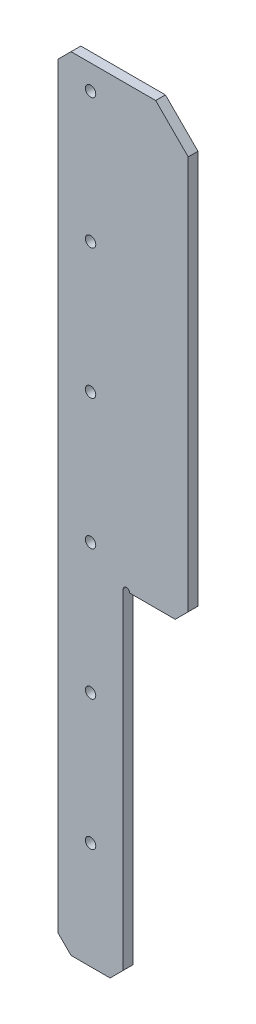
SolidWorks part; units mm, degrees
ref_plane "前视基准面" through (0, 0, 0) normal (0, 0, 1) x (1, 0, 0)
ref_plane "上视基准面" through (0, 0, 0) normal (0, 1, 0) x (1, 0, 0)
ref_plane "右视基准面" through (0, 0, 0) normal (1, 0, 0) x (0, 0, -1)
sketch "草图1" plane through (0, 0, 0) normal (0, 0, 1) x (1, 0, 0)
  line L0 (-20, 135) -> (-20, -105.4)
  line L1 (-20, -105.4) -> (0, -105.4)
  line L2 (0, -105.4) -> (0, 0)
  line L3 (0, 0) -> (20, 0)
  line L4 (20, 0) -> (20, 135)
  line L5 (20, 135) -> (-20, 135)
  point P6 (0, 135)
  dimension "D1" = 40
  dimension "D2" = 135
  dimension "D3" = 240.4
extrude "凸台-拉伸1" add sketch "草图1" along normal mid plane 3
sketch "草图2" plane through (0, 0, 1.5) normal (0, 0, 1) x (1, 0, 0)
  line L0 (20, 135) -> (-20, 135) construction
  line L1 (-20, 135) -> (-20, -105.4) construction
  circle A0 centre (-10, 127.5) radius 1.6
  dimension "D1" = 7.5
  dimension "D2" = 10
  dimension "D3" = 3.2
extrude "切除-拉伸1" cut sketch "草图2" against normal through all
pattern_linear "阵列(线性)1" count 6 spacing 40 along (0, -1, 0) of "切除-拉伸1"
chamfer "倒角1" distance 10 angle 45 1 edges at (20, 135, 0)
chamfer "倒角2" distance 4 angle 45 4 edges at (20, 0, 0) (0, -105.4, 0) (-20, -105.4, 0) (-20, 135, 0)
sketch "草图3" plane through (0, 0, 1.5) normal (0, 0, 1) x (1, 0, 0)
  line L0 (0, 0) -> (16, 0) construction
  circle A0 centre (1, 0) radius 1
  dimension "D1" = 2
extrude "切除-拉伸2" cut sketch "草图3" against normal through all
